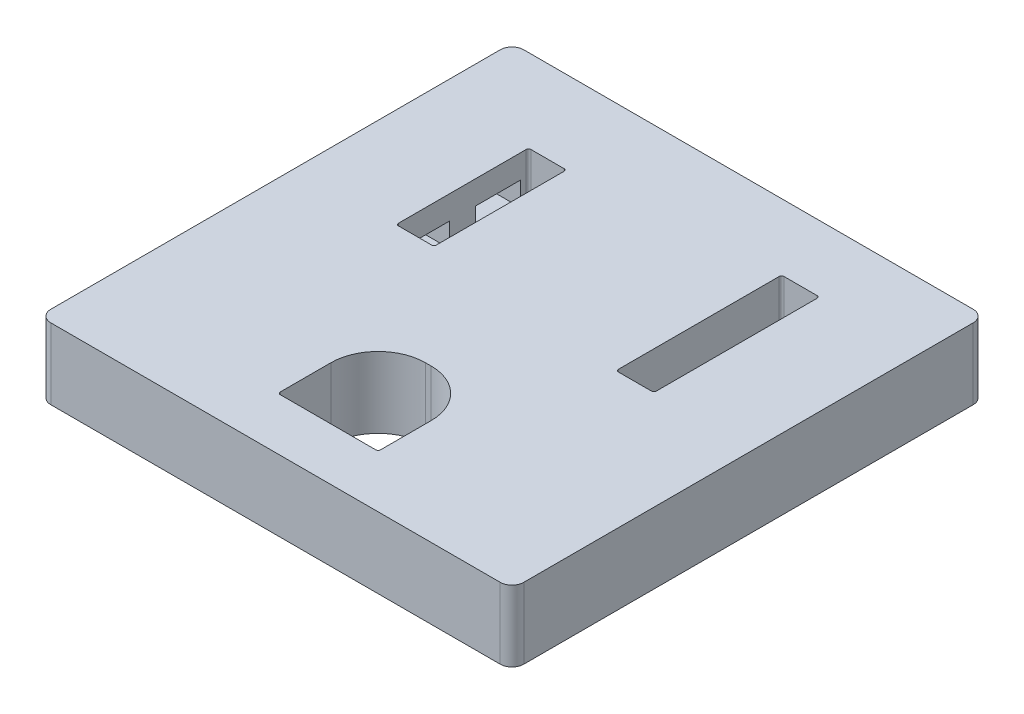
SolidWorks part; units mm, degrees
ref_plane "Front Plane" through (0, 0, 0) normal (0, 0, 1) x (1, 0, 0)
ref_plane "Top Plane" through (0, 0, 0) normal (0, 1, 0) x (1, 0, 0)
ref_plane "Right Plane" through (0, 0, 0) normal (1, 0, 0) x (0, 0, -1)
sketch "Sketch1" plane through (0, 0, 0) normal (0, 1, 0) x (1, 0, 0)
  line L1 (0.635, 0) -> (24.765, 0)
  line L2 (0, 0.635) -> (0, 24.765)
  line L3 (0.635, 25.4) -> (24.765, 25.4)
  line L4 (25.4, 0.635) -> (25.4, 24.765)
  arc A0 (24.765, 25.4) -> (25.4, 24.765) centre (24.765, 24.765) cw
  arc A1 (24.765, 0) -> (25.4, 0.635) centre (24.765, 0.635) ccw
  arc A2 (0.635, 0) -> (0, 0.635) centre (0.635, 0.635) cw
  arc A3 (0, 24.765) -> (0.635, 25.4) centre (0.635, 24.765) cw
  point P7 (25.4, 25.4)
  point P10 (25.4, 0)
  point P13 (0, 0)
  point P16 (0, 25.4)
  dimension "D3" = 0.635
  dimension "D1" = 25.4
  dimension "D2" = 25.4
extrude "Boss-Extrude1" add sketch "Sketch1" along normal blind 3.81
sketch "Sketch2" plane through (0, 3.81, 0) normal (0, 1, 0) x (1, 0, 0)
  line L0 (0, 24.765) -> (0, 0.635) construction
  line L1 (10.1346, 2.8194) -> (15.2654, 2.8194)
  line L2 (10.0076, 2.9464) -> (10.0076, 5.6642)
  line L3 (12.5476, 8.2042) -> (12.8524, 8.2042)
  line L4 (15.3924, 2.9464) -> (15.3924, 5.6642)
  line L5 (0.635, 0) -> (24.765, 0) construction
  line L6 (24.765, 25.4) -> (0.635, 25.4) construction
  line L7 (5.461, 20.955) -> (7.239, 20.955)
  line L8 (5.334, 20.828) -> (5.334, 20.5105)
  line L9 (5.461, 13.843) -> (7.239, 13.843)
  line L10 (7.366, 20.828) -> (7.366, 13.97)
  line L11 (18.161, 21.844) -> (19.939, 21.844)
  line L12 (18.034, 21.717) -> (18.034, 13.081)
  line L13 (18.161, 12.954) -> (19.939, 12.954)
  line L14 (20.066, 21.717) -> (20.066, 20.5105)
  line L18 (5.334, 14.2875) -> (5.334, 13.97)
  line L22 (20.066, 14.2875) -> (20.066, 13.081)
  line L26 (5.334, 20.5105) -> (5.334, 18.0975)
  line L30 (20.066, 18.0975) -> (20.066, 16.7005)
  line L31 (5.334, 18.0975) -> (5.334, 16.7005)
  line L32 (5.334, 16.7005) -> (5.334, 14.2875)
  line L33 (20.066, 14.2875) -> (20.066, 16.7005)
  line L34 (20.066, 18.0975) -> (20.066, 20.5105)
  arc A0 (15.2654, 2.8194) -> (15.3924, 2.9464) centre (15.2654, 2.9464) ccw
  arc A1 (10.1346, 2.8194) -> (10.0076, 2.9464) centre (10.1346, 2.9464) cw
  arc A2 (12.8524, 8.2042) -> (15.3924, 5.6642) centre (12.8524, 5.6642) cw
  arc A3 (10.0076, 5.6642) -> (12.5476, 8.2042) centre (12.5476, 5.6642) cw
  arc A4 (18.034, 13.081) -> (18.161, 12.954) centre (18.161, 13.081) ccw
  arc A5 (19.939, 12.954) -> (20.066, 13.081) centre (19.939, 13.081) ccw
  arc A6 (19.939, 21.844) -> (20.066, 21.717) centre (19.939, 21.717) cw
  arc A7 (18.161, 21.844) -> (18.034, 21.717) centre (18.161, 21.717) ccw
  arc A8 (7.239, 20.955) -> (7.366, 20.828) centre (7.239, 20.828) cw
  arc A9 (5.461, 20.955) -> (5.334, 20.828) centre (5.461, 20.828) ccw
  arc A10 (5.334, 13.97) -> (5.461, 13.843) centre (5.461, 13.97) ccw
  arc A11 (7.239, 13.843) -> (7.366, 13.97) centre (7.239, 13.97) ccw
  point P42 (12.7, 25.4)
  dimension "D5" = 0.127
  dimension "D6" = 2.54
  dimension "D27" = 0.127
  dimension "D1" = 10.0076
  dimension "D2" = 15.3924
  dimension "D3" = 2.8194
  dimension "D4" = 8.2042
  dimension "D7" = 13.843
  dimension "D8" = 20.955
  dimension "D9" = 12.954
  dimension "D10" = 21.844
  dimension "D11" = 5.334
  dimension "D12" = 5.334
  dimension "D13" = 7.366
  dimension "D14" = 7.366
extrude "Cut-Extrude1" cut sketch "Sketch2" against normal through all
sketch "Sketch4" plane through (5.334, 0, 0) normal (1, 0, 0) x (0, 0, -1)
  line L0 (0, 3.81) -> (0, 0) construction
  line L1 (14.2875, 2.54) -> (16.7005, 2.54)
  line L2 (14.2875, 2.54) -> (14.2875, 1.27)
  line L3 (14.2875, 1.27) -> (16.7005, 1.27)
  line L4 (16.7005, 2.54) -> (16.7005, 1.27)
  line L5 (18.0975, 2.54) -> (20.5105, 2.54)
  line L6 (18.0975, 2.54) -> (18.0975, 1.27)
  line L7 (18.0975, 1.27) -> (20.5105, 1.27)
  line L8 (20.5105, 2.54) -> (20.5105, 1.27)
  line L9 (0.635, 3.81) -> (24.765, 3.81) construction
  line L10 (0.635, 0) -> (24.765, 0) construction
  dimension "D1" = 18.0975
  dimension "D2" = 16.7005
  dimension "D3" = 14.2875
  dimension "D4" = 20.5105
  dimension "D5" = 1.27
  dimension "D6" = 1.27
  dimension "D7" = 1.27
  dimension "D8" = 1.27
extrude "Cut-Extrude2" cut sketch "Sketch4" against normal blind 2.2352
sketch "Sketch6" plane through (20.066, 0, 0) normal (-1, 0, 0) x (0, 0, 1)
  line L0 (0, 3.81) -> (0, 0) construction
  line L1 (-14.2875, 2.54) -> (-16.7005, 2.54)
  line L2 (-14.2875, 2.54) -> (-14.2875, 1.27)
  line L3 (-14.2875, 1.27) -> (-16.7005, 1.27)
  line L4 (-16.7005, 2.54) -> (-16.7005, 1.27)
  line L5 (-18.0975, 2.54) -> (-20.5105, 2.54)
  line L6 (-18.0975, 2.54) -> (-18.0975, 1.27)
  line L7 (-18.0975, 1.27) -> (-20.5105, 1.27)
  line L8 (-20.5105, 2.54) -> (-20.5105, 1.27)
  line L9 (-0.635, 3.81) -> (-24.765, 3.81) construction
  line L10 (-0.635, 0) -> (-24.765, 0) construction
  dimension "D1" = 14.2875
  dimension "D2" = 20.5105
  dimension "D3" = 16.7005
  dimension "D4" = 18.0975
  dimension "D5" = 1.27
  dimension "D6" = 1.27
  dimension "D7" = 1.27
  dimension "D8" = 1.27
extrude "Cut-Extrude3" cut sketch "Sketch6" against normal blind 2.2352
